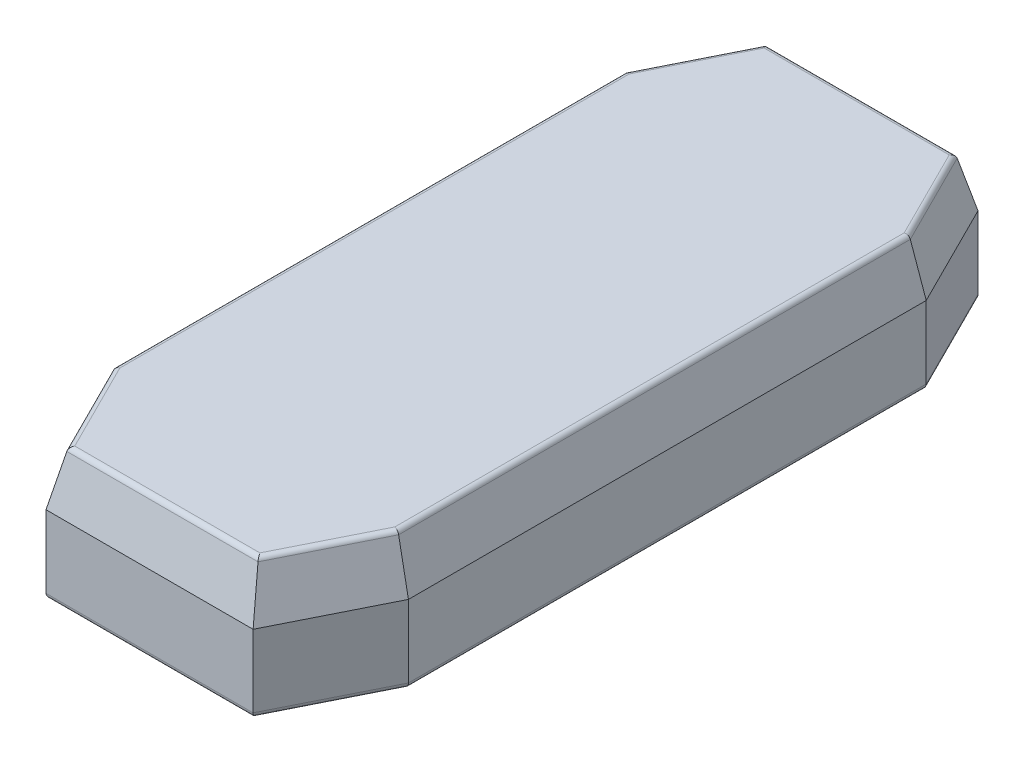
SolidWorks part; units mm, degrees
ref_plane "Front Plane" through (0, 0, 0) normal (0, 0, 1) x (1, 0, 0)
ref_plane "Top Plane" through (0, 0, 0) normal (0, 1, 0) x (1, 0, 0)
ref_plane "Right Plane" through (0, 0, 0) normal (1, 0, 0) x (0, 0, -1)
sketch "Sketch1" plane through (0, 0, 0) normal (0, 1, 0) x (1, 0, 0)
  line L0 (-7.62, 12.7) -> (-5.08, 17.78)
  line L1 (-5.08, 17.78) -> (5.08, 17.78)
  line L2 (-7.62, 12.7) -> (-7.62, -12.7)
  line L3 (-5.08, -17.78) -> (5.08, -17.78)
  line L4 (7.62, 12.7) -> (7.62, -12.7)
  line L5 (-7.62, 17.78) -> (7.62, -17.78) construction
  line L6 (-7.62, -17.78) -> (7.62, 17.78) construction
  line L7 (5.08, 17.78) -> (7.62, 12.7)
  line L8 (5.08, -17.78) -> (7.62, -12.7)
  line L9 (-7.62, -12.7) -> (-5.08, -17.78)
  point P0 (0, 0)
  dimension "D1" = 15.24
  dimension "D2" = 35.56
  dimension "D3" = 2.54
  dimension "D4" = 5.08
  dimension "D5" = 2.54
  dimension "D6" = 5.08
  dimension "D7" = 2.54
  dimension "D8" = 5.08
  dimension "D9" = 5.08
  dimension "D10" = 2.54
extrude "Boss-Extrude1" add sketch "Sketch1" along normal blind 2.54 draft 15
sketch "Stem" plane through (0, 0, 0) normal (0, -1, 0) x (1, 0, 0)
  line L1 (-0.5625, 2.075) -> (0.5625, 2.075)
  line L2 (-0.5625, 2.075) -> (-0.5625, -2.075)
  line L3 (-0.5625, -2.075) -> (0.5625, -2.075)
  line L4 (0.5625, 2.075) -> (0.5625, -2.075)
  line L5 (-0.5625, 2.075) -> (0.5625, -2.075) construction
  line L6 (-0.5625, -2.075) -> (0.5625, 2.075) construction
  line L7 (2.0625, 0.6625) -> (-2.0625, 0.6625)
  line L8 (2.0625, 0.6625) -> (2.0625, -0.6625)
  line L9 (2.0625, -0.6625) -> (-2.0625, -0.6625)
  line L10 (-2.0625, 0.6625) -> (-2.0625, -0.6625)
  line L11 (2.0625, 0.6625) -> (-2.0625, -0.6625) construction
  line L12 (2.0625, -0.6625) -> (-2.0625, 0.6625) construction
  line L13 (-2.5, 2.5) -> (2.5, 2.5)
  line L14 (-3, 2) -> (-3, -2)
  line L15 (-2.5, -2.5) -> (2.5, -2.5)
  line L16 (3, 2) -> (3, -2)
  line L17 (-3, 2.5) -> (3, -2.5) construction
  line L18 (-3, -2.5) -> (3, 2.5) construction
  arc A0 (-3, -2) -> (-2.5, -2.5) centre (-2.5, -2) ccw
  arc A1 (-2.5, 2.5) -> (-3, 2) centre (-2.5, 2) ccw
  arc A2 (2.5, -2.5) -> (3, -2) centre (2.5, -2) ccw
  arc A3 (2.5, 2.5) -> (3, 2) centre (2.5, 2) cw
  point P0 (0, 0)
  point P6 (0, 0)
  point P11 (0, 0)
  dimension "D7" = 0.5
  dimension "D1" = 4.15
  dimension "D2" = 1.125
  dimension "D3" = 1.325
  dimension "D4" = 4.125
  dimension "D5" = 5
  dimension "D6" = 6
extrude "Boss-Extrude2" add sketch "Stem" along normal blind 3.8 contours A3 L13 A1 L14 A0 L15 A2 L16 L10 L7 L2 L1 L4 L8 L9 L3
fillet "Fillet2" radius 0.1 8 edges at (-2.8536, -3.8, -2.3536) (-3, -3.8, 0) (-2.8536, -3.8, 2.3536) (0, -3.8, 2.5) (2.8536, -3.8, 2.3536) (3, -3.8, 0) (2.8536, -3.8, -2.3536) (0, -3.8, -2.5)
chamfer "Chamfer1" distance 0.2 angle 45 11 edges at (-0.5625, -3.8, -1.3688) (-1.3125, -3.8, -0.6625) (-2.0625, -3.8, 0) (0.5625, -3.8, -1.3688) (1.3125, -3.8, -0.6625) (2.0625, -3.8, 0) (1.3125, -3.8, 0.6625) (0.5625, -3.8, 1.3687) (0, -3.8, 2.075) (-0.5625, -3.8, 1.3687) (-1.3125, -3.8, 0.6625)
sketch "Sketch3" plane through (0, 0, 0) normal (0, -1, 0) x (1, 0, 0)
  line L0 (-7.62, 12.7) -> (-7.62, -12.7)
  line L1 (-7.62, -12.7) -> (-5.08, -17.78)
  line L2 (-5.08, -17.78) -> (5.08, -17.78)
  line L3 (5.08, -17.78) -> (7.62, -12.7)
  line L4 (7.62, -12.7) -> (7.62, 12.7)
  line L5 (7.62, 12.7) -> (5.08, 17.78)
  line L6 (5.08, 17.78) -> (-5.08, 17.78)
  line L7 (-5.08, 17.78) -> (-7.62, 12.7)
  line L44 (-6.35, -12.4002) -> (-4.2951, -16.51)
  line L45 (-4.2951, -16.51) -> (4.2951, -16.51)
  line L46 (4.2951, -16.51) -> (6.35, -12.4002)
  line L47 (6.35, -12.4002) -> (6.35, 12.4002)
  line L48 (6.35, 12.4002) -> (4.2951, 16.51)
  line L49 (4.2951, 16.51) -> (-4.2951, 16.51)
  line L50 (-4.2951, 16.51) -> (-6.35, 12.4002)
  line L51 (-6.35, 12.4002) -> (-6.35, -12.4002)
  line L52 (-6.35, -12.4002) -> (-4.2951, -16.51)
  line L53 (-4.2951, -16.51) -> (4.2951, -16.51)
  line L54 (4.2951, -16.51) -> (6.35, -12.4002)
  line L55 (6.35, -12.4002) -> (6.35, 12.4002)
  line L56 (6.35, 12.4002) -> (4.2951, 16.51)
  line L57 (4.2951, 16.51) -> (-4.2951, 16.51)
  line L58 (-4.2951, 16.51) -> (-6.35, 12.4002)
  line L59 (-6.35, 12.4002) -> (-6.35, -12.4002)
  dimension "D1" = 1.27
extrude "Boss-Extrude3" add sketch "Sketch3" along normal blind 3.8
fillet "Fillet3" radius 0.25 16 edges at (0, -3.8, -16.51) (5.3225, -3.8, -14.4551) (6.35, -3.8, 0) (5.3225, -3.8, 14.4551) (0, -3.8, 16.51) (-5.3225, -3.8, 14.4551) (-6.35, -3.8, 0) (-5.3225, -3.8, -14.4551) (0, -3.8, 17.78) (6.35, -3.8, 15.24) (7.62, -3.8, 0) (6.35, -3.8, -15.24) (0, -3.8, -17.78) (-6.35, -3.8, -15.24) (-7.62, -3.8, 0) (-6.35, -3.8, 15.24)
fillet "Fillet5" radius 0.5 16 edges at (0, 0, 2.5) (-2.8536, 0, 2.3536) (-3, 0, 0) (-2.8536, 0, -2.3536) (0, 0, -2.5) (2.8536, 0, -2.3536) (3, 0, 0) (2.8536, 0, 2.3536) (-5.3225, 0, 14.4551) (0, 0, 16.51) (5.3225, 0, 14.4551) (6.35, 0, 0) (5.3225, 0, -14.4551) (0, 0, -16.51) (-5.3225, 0, -14.4551) (-6.35, 0, 0)
fillet "Fillet6" radius 0.1 12 edges at (-1.3125, 0, 0.6625) (-0.5625, 0, 1.3687) (0, 0, 2.075) (0.5625, 0, 1.3687) (1.3125, 0, 0.6625) (2.0625, 0, 0) (1.3125, 0, -0.6625) (0.5625, 0, -1.3688) (0, 0, -2.075) (-0.5625, 0, -1.3688) (-1.3125, 0, -0.6625) (-2.0625, 0, 0)
fillet "Fillet7" radius 0.25 8 edges at (5.7994, 2.54, -14.8194) (6.9394, 2.54, 0) (5.7994, 2.54, 14.8194) (0, 2.54, 17.0994) (-5.7994, 2.54, 14.8194) (-6.9394, 2.54, 0) (-5.7994, 2.54, -14.8194) (0, 2.54, -17.0994)
sketch "Sketch4" plane through (0, 2.54, 0) normal (0, 1, 0) x (1, 0, 0)
  line L24 (5.7316, -12.2542) -> (5.7316, 12.2542)
  line L25 (5.7316, 12.2542) -> (3.9129, 15.8916)
  line L26 (3.9129, 15.8916) -> (-3.9129, 15.8916)
  line L27 (-3.9129, 15.8916) -> (-5.7316, 12.2542)
  line L28 (-5.7316, 12.2542) -> (-5.7316, -12.2542)
  line L29 (-5.7316, -12.2542) -> (-3.9129, -15.8916)
  line L30 (-3.9129, -15.8916) -> (3.9129, -15.8916)
  line L31 (3.9129, -15.8916) -> (5.7316, -12.2542)
  line L32 (5.7316, -12.2542) -> (5.7316, 12.2542)
  line L33 (5.7316, 12.2542) -> (3.9129, 15.8916)
  line L34 (3.9129, 15.8916) -> (-3.9129, 15.8916)
  line L35 (-3.9129, 15.8916) -> (-5.7316, 12.2542)
  line L36 (-5.7316, 12.2542) -> (-5.7316, -12.2542)
  line L37 (-5.7316, -12.2542) -> (-3.9129, -15.8916)
  line L38 (-3.9129, -15.8916) -> (3.9129, -15.8916)
  line L39 (3.9129, -15.8916) -> (5.7316, -12.2542)
  dimension "D1" = 1.016
